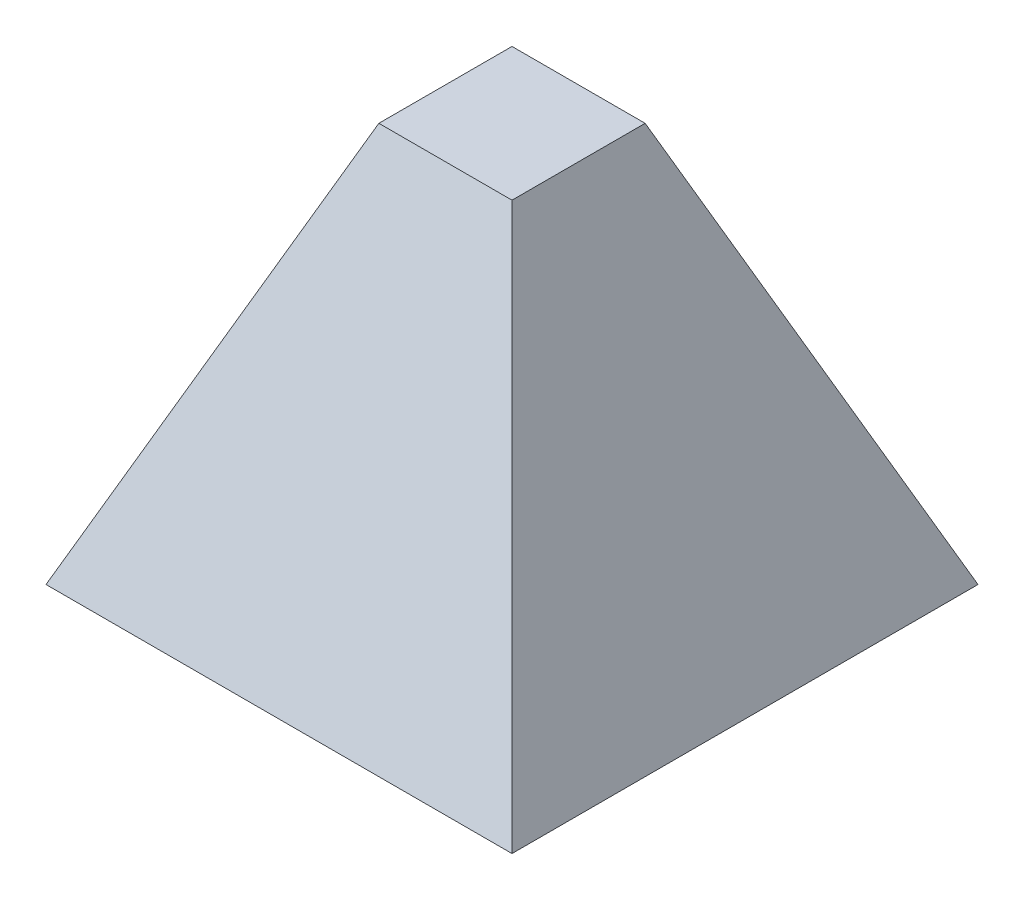
SolidWorks part; units mm, degrees
ref_plane "前视基准面" through (0, 0, 0) normal (0, 0, 1) x (1, 0, 0)
ref_plane "上视基准面" through (0, 0, 0) normal (0, 1, 0) x (1, 0, 0)
ref_plane "右视基准面" through (0, 0, 0) normal (1, 0, 0) x (0, 0, -1)
other "Configuration Table"
sketch "草图1" plane through (0, 0, 0) normal (0, 1, 0) x (1, 0, 0)
  line L1 (-70, -70) -> (70, -70)
  line L2 (-70, -70) -> (-70, 70)
  line L3 (-70, 70) -> (70, 70)
  line L4 (70, -70) -> (70, 70)
extrude "凸台-拉伸1" add sketch "草图1" along normal blind 120 draft 22.62
shell "抽壳1" thickness 3
sketch "000000000" plane through (0, 0, 0) normal (0, 1, 0) x (1, 0, 0)
  line L4 (-67, -67) -> (67, -67)
  line L5 (-67, -67) -> (-67, 67)
  line L6 (67, 67) -> (67, -67)
  line L7 (-67, 67) -> (67, 67)
  point P3 (0, 0)
  point P10 (67, 0)
  point P12 (-67, 0)
extrude "凸台-拉伸2" add sketch "000000000" along normal blind 10 draft 22.62 separate body
